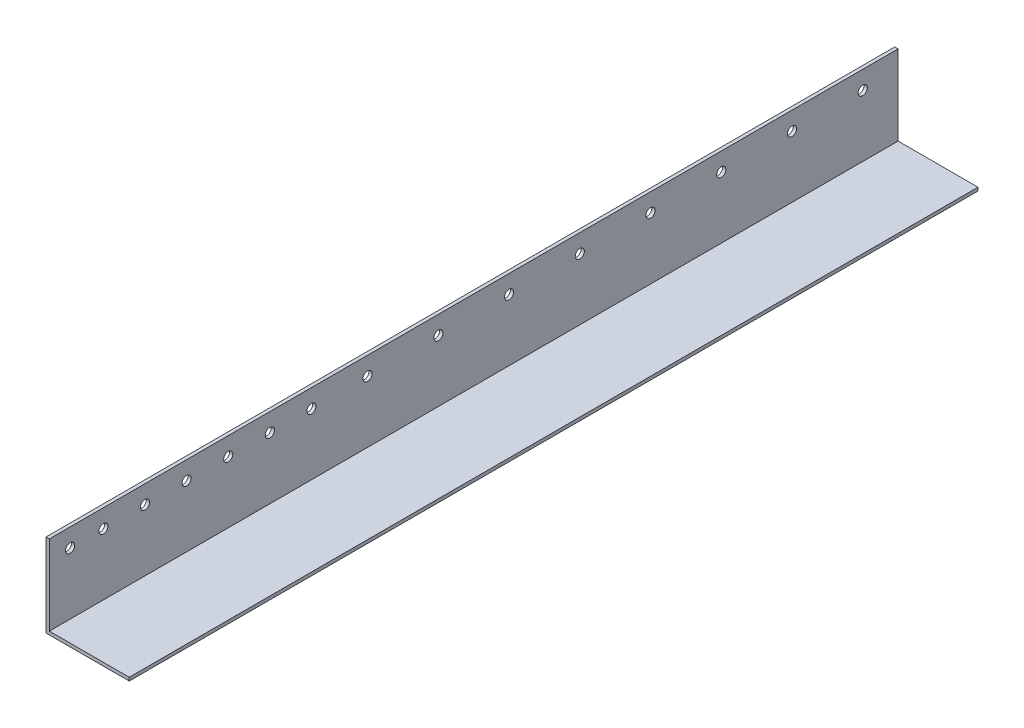
SolidWorks part; units mm, degrees
ref_plane "Front Plane" through (0, 0, 0) normal (0, 0, 1) x (1, 0, 0)
ref_plane "Top Plane" through (0, 0, 0) normal (0, 1, 0) x (1, 0, 0)
ref_plane "Right Plane" through (0, 0, 0) normal (1, 0, 0) x (0, 0, -1)
sketch "Sketch1" plane through (0, 0, 0) normal (0, 0, 1) x (1, 0, 0)
  line L0 (0, 0) -> (50, 0)
  line L1 (50, 0) -> (50, 2)
  line L2 (50, 2) -> (2, 2)
  line L3 (2, 2) -> (2, 50)
  line L4 (2, 50) -> (0, 50)
  line L5 (0, 50) -> (0, 0)
extrude "Boss-Extrude1" add sketch "Sketch1" along normal blind 510
sketch "Sketch2" plane through (0, 0, 0) normal (1, 0, 0) x (0, 0, -1)
  circle A0 centre (-21.25, 39) radius 2.75
  circle A1 centre (-63.75, 39) radius 2.75
  circle A2 centre (-106.25, 39) radius 2.75
  circle A3 centre (-148.75, 39) radius 2.75
  circle A4 centre (-191.25, 39) radius 2.75
  circle A5 centre (-233.75, 39) radius 2.75
  circle A6 centre (-276.25, 39) radius 2.75
  circle A7 centre (-318.75, 39) radius 2.75
  circle A8 centre (-352.5, 39) radius 2.75
  circle A9 centre (-377.5, 39) radius 2.75
  circle A10 centre (-402.5, 39) radius 2.75
  circle A11 centre (-427.5, 39) radius 2.75
  circle A12 centre (-452.5, 39) radius 2.75
  circle A13 centre (-477.5, 39) radius 2.75
  circle A14 centre (-497.5, 39) radius 2.75
extrude "Cut-Extrude1" cut sketch "Sketch2" against normal mid plane 10
